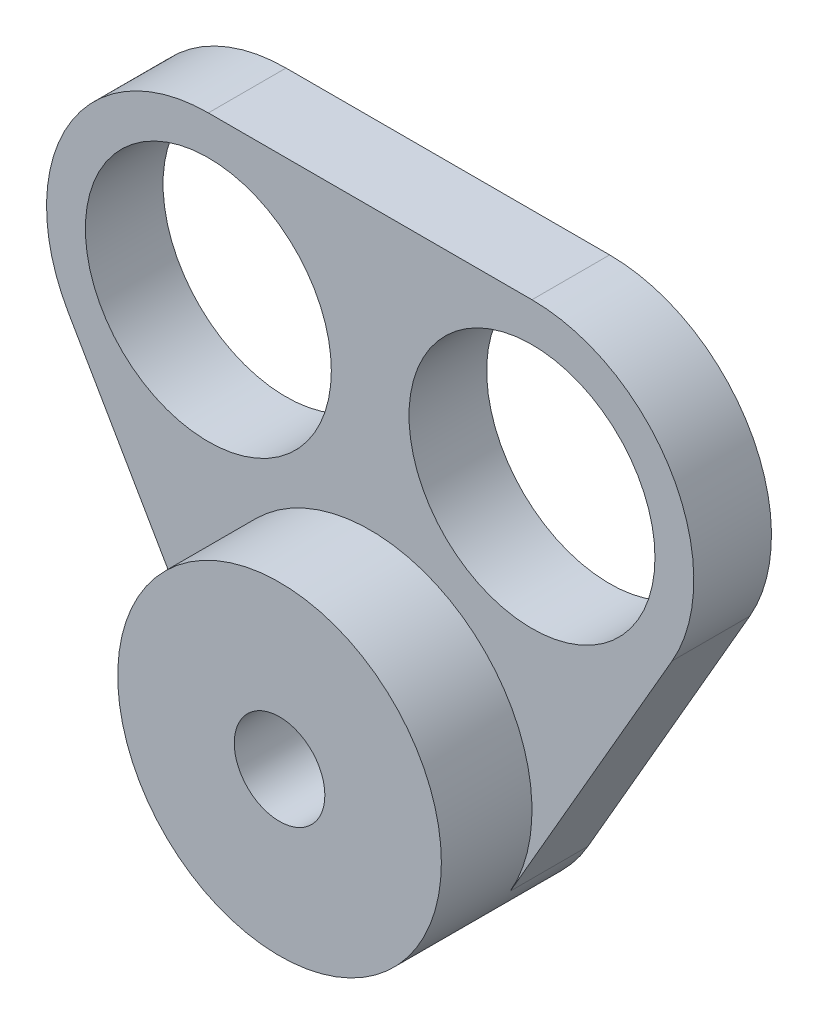
SolidWorks part; units mm, degrees
ref_plane "Alzado" through (0, 0, 0) normal (0, 0, 1) x (1, 0, 0)
ref_plane "Planta" through (0, 0, 0) normal (0, 1, 0) x (1, 0, 0)
ref_plane "Vista lateral" through (0, 0, 0) normal (1, 0, 0) x (0, 0, -1)
sketch "Croquis1" plane through (0, 0, 0) normal (0, 0, 1) x (1, 0, 0)
  line L0 (0, 0) -> (12.5, 21.6506) construction
  line L1 (12.5, 21.6506) -> (-12.5, 21.6506) construction
  line L2 (-12.5, 21.6506) -> (0, 0) construction
  line L3 (0, 0) -> (12.5, 21.6506) construction
  line L4 (12.5, 21.6506) -> (25.4113, 14.1963) construction
  line L5 (12.5, 21.6506) -> (0, 0) construction
  line L6 (0, 0) -> (14.6404, -8.4526) construction
  line L7 (10.8253, -6.25) -> (23.3253, 15.4006)
  line L8 (12.5, 21.6506) -> (-12.5, 21.6506) construction
  line L9 (-12.5, 21.6506) -> (-12.5, 40.0051) construction
  line L10 (12.5, 21.6506) -> (12.5, 40.0051) construction
  line L11 (-12.5, 34.1506) -> (12.5, 34.1506)
  line L12 (-12.5, 21.6506) -> (0, 0) construction
  line L13 (0, 0) -> (-19.3941, -11.1972) construction
  line L14 (0, 0) -> (-12.5, 21.6506) construction
  line L15 (-12.5, 21.6506) -> (-31.25, 10.8253) construction
  line L16 (-23.3253, 15.4006) -> (-10.8253, -6.25)
  circle A0 centre (-12.5, 21.6506) radius 12.5
  circle A1 centre (12.5, 21.6506) radius 12.5
  circle A2 centre (0, 0) radius 9.5
  circle A3 centre (-12.5, 21.6506) radius 9.5
  circle A4 centre (12.5, 21.6506) radius 9.5
  circle A5 centre (0, 0) radius 12.5
  dimension "D4" = 25
  dimension "D5" = 19
  dimension "D6" = 25
  dimension "D7" = 19
  dimension "D8" = 19
  dimension "D9" = 25
  dimension "D1" = 25
  dimension "D2" = 25
  dimension "D3" = 25
extrude "Saliente-Extruir1" add sketch "Croquis1" along normal blind 6 contours A0 A3 | A1 L11 A0 | A1 A4 | A5 A1 A0 | A5 A0 L16 | A5 A2 | A5 L7 A1
sketch "Croquis2" plane through (0, 0, 6) normal (0, 0, 1) x (1, 0, 0)
  circle A0 centre (0, 0) radius 12.5
  circle A1 centre (0, 0) radius 3.5
  dimension "D1" = 25
  dimension "D2" = 7
extrude "Saliente-Extruir3" add sketch "Croquis2" along normal blind 7
